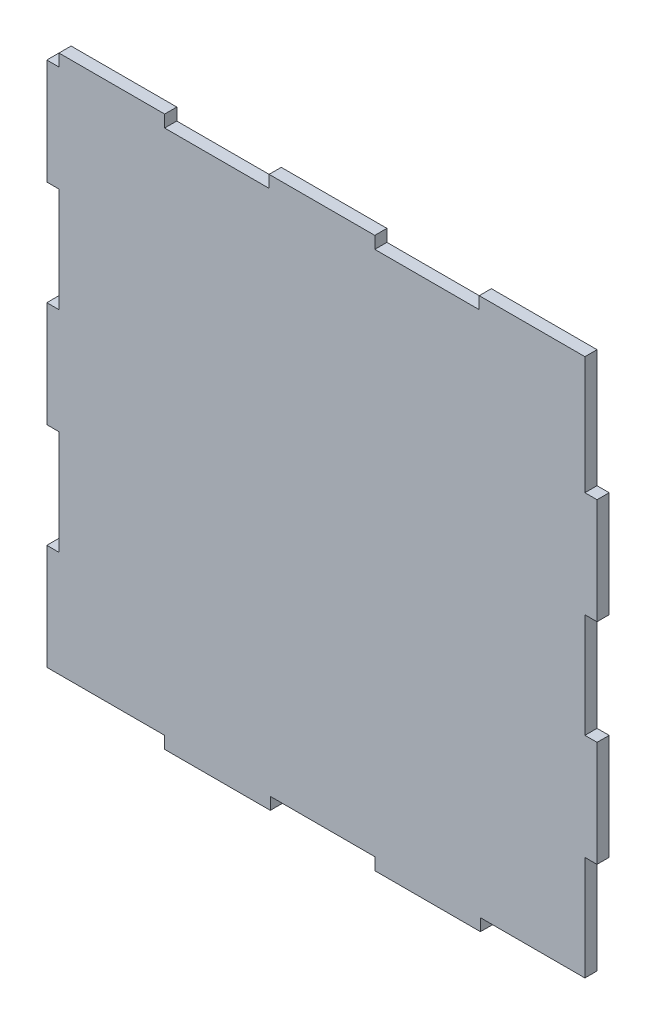
SolidWorks part; units mm, degrees
ref_plane "Front Plane" through (0, 0, 0) normal (0, 0, 1) x (1, 0, 0)
ref_plane "Top Plane" through (0, 0, 0) normal (0, 1, 0) x (1, 0, 0)
ref_plane "Right Plane" through (0, 0, 0) normal (1, 0, 0) x (0, 0, -1)
sketch "Sketch2" plane through (0, 0, 0) normal (0, 0, 1) x (1, 0, 0)
  line L0 (0, 38.675) -> (0, 65) construction
  line L1 (-38.675, 0) -> (-65, 0) construction
  line L2 (0, -38.675) -> (0, -65) construction
  line L7 (11.1493, -38.675) -> (-11.1493, -38.675) construction
  line L8 (38.675, -11.1493) -> (38.675, 11.1493) construction
  line L21 (11.1493, 38.675) -> (-11.1493, 38.675) construction
  line L45 (-38.675, -11.1493) -> (-38.675, 11.1493) construction
  line L46 (38.675, -38.675) -> (-38.675, 38.675) construction
  line L99 (38.675, 38.675) -> (-38.675, -38.675) construction
  line L116 (65, 38.88) -> (68, 38.88)
  line L117 (-65, -38.88) -> (-65, -13.06)
  line L118 (68, 38.88) -> (68, 12.76)
  line L119 (68, 12.76) -> (65, 12.76)
  line L120 (38.675, 0) -> (65, 0) construction
  line L121 (-13.06, 65) -> (-38.88, 65)
  line L122 (-38.88, 65) -> (-38.88, 68)
  line L123 (-13.06, 65) -> (-13.06, 68)
  line L124 (-13.06, 68) -> (13.06, 68)
  line L125 (13.06, 65) -> (13.06, 68)
  line L126 (38.88, 65) -> (38.88, 68)
  line L127 (38.88, 68) -> (65, 68)
  line L128 (38.88, 65) -> (13.06, 65)
  line L129 (-65, 66.5) -> (-39.18, 66.5) construction
  line L130 (-39.18, 66.5) -> (-38.88, 66.5) construction
  line L131 (-65, 38.88) -> (-68, 38.88)
  line L132 (-65, 13.06) -> (-68, 13.06)
  line L133 (-65, -13.06) -> (-68, -13.06)
  line L134 (-68, 13.06) -> (-68, -13.06)
  line L135 (-65, -38.88) -> (-68, -38.88)
  line L136 (-68, -65) -> (-68, -38.88)
  line L137 (-65, 13.06) -> (-65, 38.88)
  line L138 (-38.88, -65) -> (-64.7, -65)
  line L139 (65, 12.76) -> (65, -13.06)
  line L140 (65, -13.06) -> (68, -13.06)
  line L141 (68, -13.06) -> (68, -39.18)
  line L142 (68, -39.18) -> (65, -39.18)
  line L143 (65, -39.18) -> (65, -65)
  line L144 (65, -65) -> (39.18, -65)
  line L145 (39.18, -65) -> (39.18, -68)
  line L146 (39.18, -68) -> (13.06, -68)
  line L147 (13.06, -68) -> (13.06, -65)
  line L148 (13.06, -65) -> (-12.76, -65)
  line L149 (-12.76, -65) -> (-12.76, -68)
  line L150 (-12.76, -68) -> (-38.88, -68)
  line L151 (-38.88, -68) -> (-38.88, -65)
  line L152 (-64.7, -65) -> (-68, -65)
  line L153 (65, 68) -> (65, 64.7)
  line L154 (65, 64.7) -> (65, 38.88)
  line L155 (-38.88, 68) -> (-65, 68)
  line L156 (-65, 68) -> (-65, 65)
  line L157 (-65, 65) -> (-68, 65)
  line L158 (-68, 65) -> (-68, 38.88)
  arc A9 (-38.675, -11.1493) -> (-11.1493, -38.675) centre (0, 0) ccw construction
  arc A10 (-11.1493, 38.675) -> (-38.675, 11.1493) centre (0, 0) ccw construction
  arc A11 (38.675, 11.1493) -> (11.1493, 38.675) centre (0, 0) ccw construction
  arc A12 (11.1493, -38.675) -> (38.675, -11.1493) centre (0, 0) ccw construction
  point P32 (0, 0)
  dimension "D3" = 0.3
  dimension "D2" = 80.5
  dimension "D1" = 77.35
  dimension "D4" = 3
  dimension "D5" = 130
extrude "Boss-Extrude1" add sketch "Sketch2" along normal blind 3
